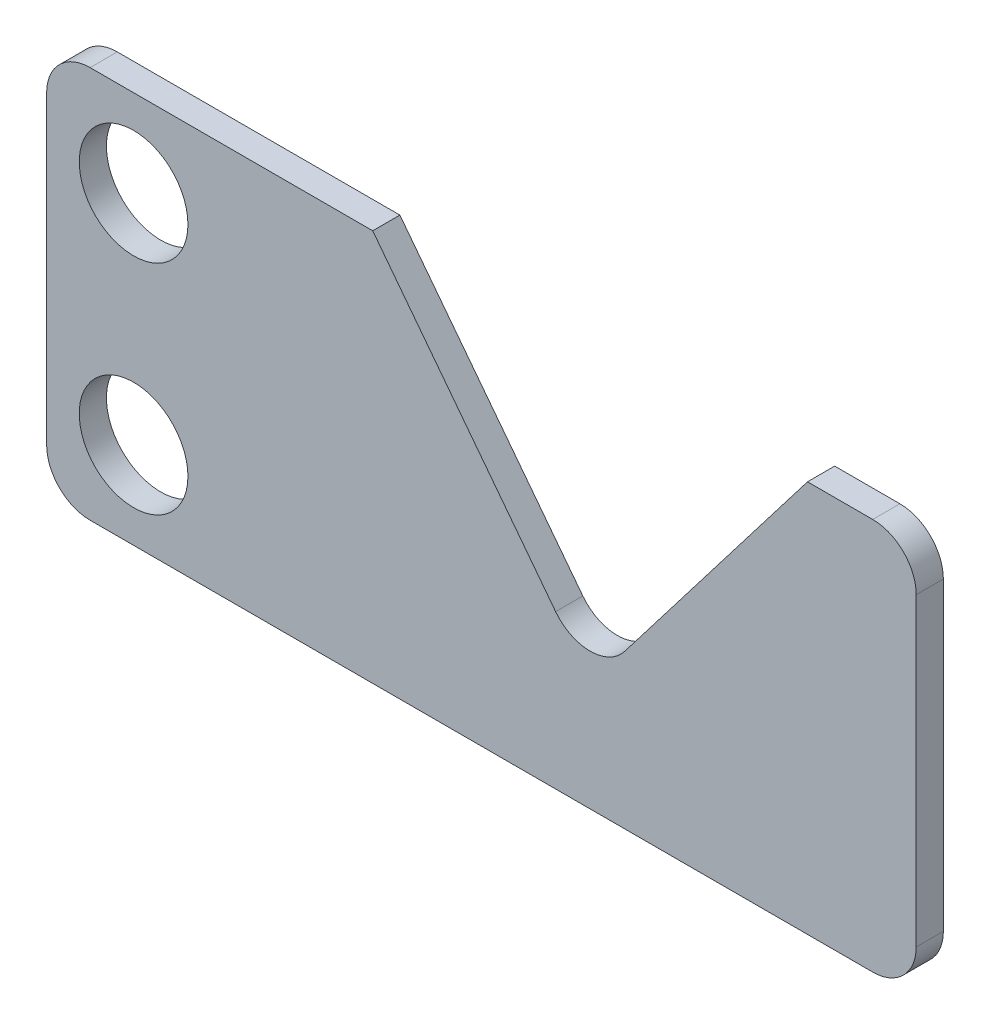
SolidWorks part; units mm, degrees
ref_plane "Front Plane" through (0, 0, 0) normal (0, 0, 1) x (1, 0, 0)
ref_plane "Top Plane" through (0, 0, 0) normal (0, 1, 0) x (1, 0, 0)
ref_plane "Right Plane" through (0, 0, 0) normal (1, 0, 0) x (0, 0, -1)
sketch "Sketch2" plane through (0, 0, 0) normal (0, 0, 1) x (1, 0, 0)
  line L0 (19.05, 22.901) -> (29.7349, 8.9762)
  line L1 (2.54, 0) -> (48.26, 0)
  line L2 (0, 2.54) -> (0, 20.361)
  line L3 (2.54, 22.901) -> (19.05, 22.901)
  line L4 (50.8, 2.54) -> (50.8, 20.361)
  line L5 (33.7651, 8.9762) -> (44.45, 22.901)
  line L6 (44.45, 22.901) -> (48.26, 22.901)
  circle A1 centre (5.08, 17.821) radius 3.175
  circle A2 centre (5.08, 5.08) radius 3.175
  arc A3 (2.54, 0) -> (0, 2.54) centre (2.54, 2.54) cw
  arc A4 (0, 20.361) -> (2.54, 22.901) centre (2.54, 20.361) cw
  arc A5 (29.7349, 8.9762) -> (33.7651, 8.9762) centre (31.75, 10.5224) ccw
  arc A6 (48.26, 22.901) -> (50.8, 20.361) centre (48.26, 20.361) cw
  arc A7 (48.26, 0) -> (50.8, 2.54) centre (48.26, 2.54) ccw
  point P9 (5.08, 5.08)
  point P11 (0, 0)
  point P14 (5.2416, 5.5295)
  point P17 (5.7545, 20.32)
  point P18 (0, 0)
  point P23 (31.75, 6.35)
  point P26 (50.8, 22.901)
  point P29 (50.8, 0)
  dimension "D6" = 5.08
  dimension "D9" = 6.35
  dimension "D10" = 6.35
  dimension "D11" = 2.54
  dimension "D1" = 50.8
  dimension "D2" = 6.35
  dimension "D3" = 25.4
  dimension "D4" = 6.35
  dimension "D5" = 75
  dimension "D7" = 5.08
  dimension "D8" = 5.08
extrude "Boss-Extrude1" add sketch "Sketch2" along normal blind 1.5875
